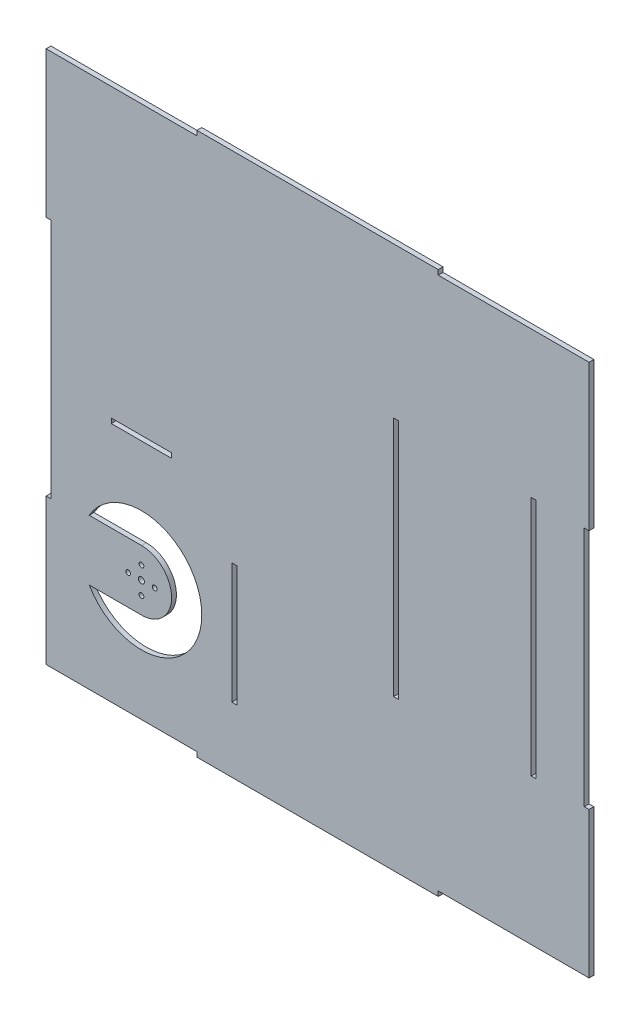
SolidWorks part; units mm, degrees
ref_plane "Front Plane" through (0, 0, 0) normal (0, 0, 1) x (1, 0, 0)
ref_plane "Top Plane" through (0, 0, 0) normal (0, 1, 0) x (1, 0, 0)
ref_plane "Right Plane" through (0, 0, 0) normal (1, 0, 0) x (0, 0, -1)
sketch "Sketch1" plane through (0, 0, 0) normal (0, 0, 1) x (1, 0, 0)
  line L0 (-225.5446, -221.4538) -> (-100.5446, -221.4538)
  line L1 (-100.5446, -221.4538) -> (-100.5446, -225.4538)
  line L2 (-100.5446, -225.4538) -> (99.4554, -225.4538)
  line L3 (99.4554, -225.4538) -> (99.4554, -221.4538)
  line L4 (99.4554, -221.4538) -> (224.4554, -221.4538)
  line L5 (224.4554, -221.4538) -> (224.4554, -100.4538)
  line L6 (224.4554, -100.4538) -> (220.4554, -100.4538)
  line L7 (220.4554, -100.4538) -> (220.4554, 99.5462)
  line L8 (220.4554, 99.5462) -> (224.4554, 99.5462)
  line L9 (224.4554, 99.5462) -> (224.4554, 220.5462)
  line L10 (224.4554, 220.5462) -> (99.4554, 220.5462)
  line L11 (99.4554, 220.5462) -> (99.4554, 224.5462)
  line L12 (99.4554, 224.5462) -> (-100.5446, 224.5462)
  line L13 (-100.5446, 224.5462) -> (-100.5446, 220.5462)
  line L14 (-100.5446, 220.5462) -> (-225.5446, 220.5462)
  line L15 (-225.5446, 220.5462) -> (-225.5446, 99.5462)
  line L16 (-225.5446, 99.5462) -> (-221.5446, 99.5462)
  line L17 (-221.5446, 99.5462) -> (-221.5446, -100.4538)
  line L18 (-221.5446, -100.4538) -> (-225.5446, -100.4538)
  line L19 (-225.5446, -100.4538) -> (-225.5446, -221.4538)
  line L20 (-146.5446, -96.4538) -> (-189.8458, -96.4538)
  line L21 (-146.5446, -146.4538) -> (-189.8458, -146.4538)
  line L23 (-171.5446, -17.4538) -> (-121.5446, -17.4538)
  line L24 (-171.5446, -17.4538) -> (-171.5446, -21.4538)
  line L25 (-171.5446, -21.4538) -> (-121.5446, -21.4538)
  line L26 (-121.5446, -17.4538) -> (-121.5446, -21.4538)
  line L27 (-67.5446, -71.4538) -> (-71.5446, -71.4538)
  line L28 (-67.5446, -71.4538) -> (-67.5446, -171.4538)
  line L29 (-67.5446, -171.4538) -> (-71.5446, -171.4538)
  line L30 (-71.5446, -71.4538) -> (-71.5446, -171.4538)
  line L31 (66.4554, -100.4538) -> (62.4554, -100.4538)
  line L32 (66.4554, -100.4538) -> (66.4554, 99.5462)
  line L33 (66.4554, 99.5462) -> (62.4554, 99.5462)
  line L34 (62.4554, -100.4538) -> (62.4554, 99.5462)
  line L35 (176.4554, 99.5462) -> (180.4554, 99.5462)
  line L36 (176.4554, 99.5462) -> (176.4554, -100.4538)
  line L37 (176.4554, -100.4538) -> (180.4554, -100.4538)
  line L38 (180.4554, 99.5462) -> (180.4554, -100.4538)
  arc A0 (-189.8458, -146.4538) -> (-189.8458, -96.4538) centre (-146.5446, -121.4538) ccw
  circle A1 centre (-135.5446, -121.4538) radius 2
  circle A2 centre (-146.5446, -110.4538) radius 2
  circle A3 centre (-157.5446, -121.4538) radius 2
  circle A4 centre (-146.5446, -132.4538) radius 2
  arc A5 (-146.5446, -146.4538) -> (-146.5446, -96.4538) centre (-146.5446, -121.4538) ccw
  circle A6 centre (-146.5446, -121.4538) radius 2.5
  dimension "D3" = 125
  dimension "D10" = 100
  dimension "D13" = 11
  dimension "D1" = 200
  dimension "D2" = 450
  dimension "D4" = 125
  dimension "D5" = 4
  dimension "D6" = 121
  dimension "D7" = 200
  dimension "D8" = 200
  dimension "D9" = 200
  dimension "D11" = 104
  dimension "D12" = 79
  dimension "D14" = 11
  dimension "D15" = 22
  dimension "D16" = 22
extrude "Boss-Extrude1" add sketch "Sketch1" along normal blind 4
